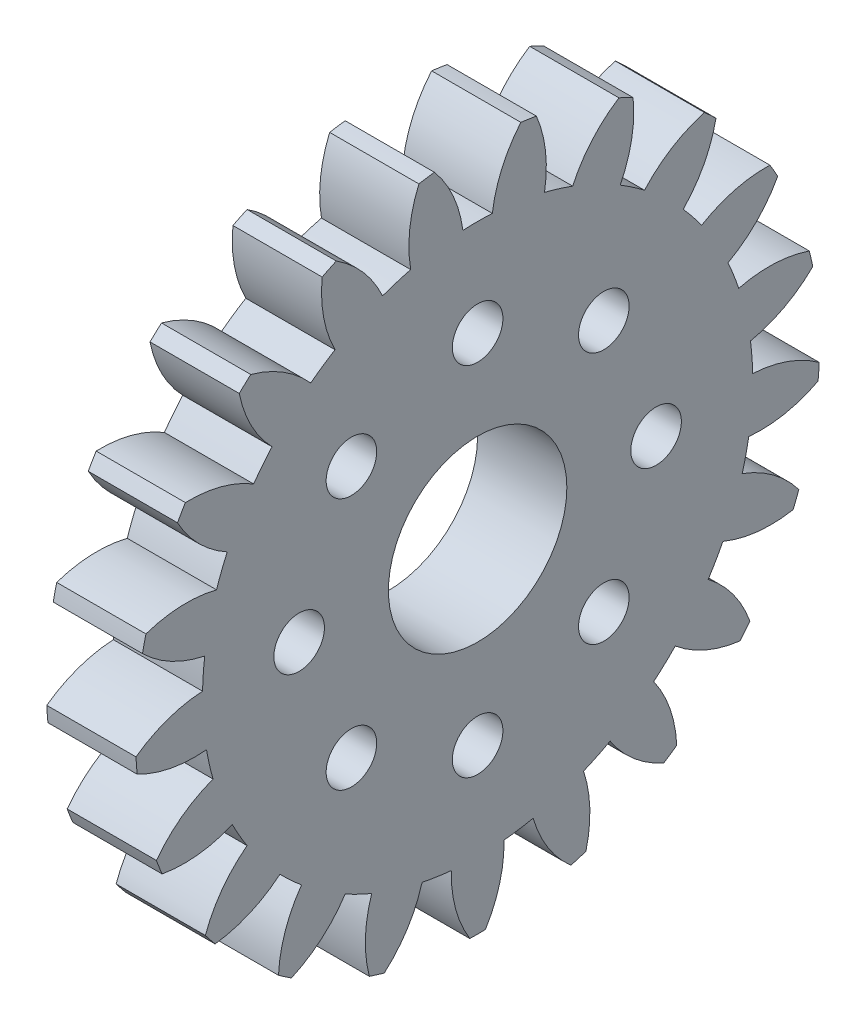
SolidWorks part; units mm, degrees
material "ﾎﾟﾘｵｷｼﾒﾁﾚﾝ(POM)ｱｾﾀｰﾙ共重合体"
ref_plane "Plane1" through (0, 0, 0) normal (0, 0, 1) x (1, 0, 0)
ref_plane "Plane2" through (0, 0, 0) normal (0, 1, 0) x (1, 0, 0)
ref_plane "Plane3" through (0, 0, 0) normal (1, 0, 0) x (0, 0, -1)
other "Configuration Table"
sketch "HoldingSke" plane through (0, 0, 0) normal (0, 1, 0) x (1, 0, 0)
  line L0 (0, 0) -> (0.9336, -0.3584)
  line L1 (-15, 0) -> (100, 0) construction
  line L2 (0, 0) -> (-2.1039, 2.3779)
  line L3 (0, 0) -> (-11.863, 4.5341)
  line L4 (0, 0) -> (8.0624, 3.0949)
  line L5 (0, 0) -> (-46.8476, -17.4728)
  line L6 (0, 0) -> (-2.4869, -1.6779)
  line L7 (-2.1039, 2.3779) -> (8.6586, 51.2059)
  line L8 (-76.2, 54.61) -> (-75.2, 54.61)
  line L9 (-71.009, 38.7566) -> (-53.1078, 45.2721)
  line L10 (-76.2, 71.12) -> (104.1128, 71.12)
  line L11 (0, 0) -> (-3, 0)
  line L12 (-76.2, 101.6) -> (-76.162, 101.6)
  line L13 (24.9733, 27.94) -> (52.9518, 28.4284)
  line L14 (24.9733, 27.94) -> (24.9743, 27.94)
  line L15 (24.9733, 27.94) -> (100.4006, 29.5858)
  line L16 (-63.627, -1) -> (-12.827, -1)
  circle A0 centre (0, 0) radius 4
  circle A1 centre (0, 0) radius 9.249
  circle A2 centre (0, 0) radius 37.5
  circle A3 centre (0, 0) radius 4
  dimension "MHD" = 18.498
  dimension "Hub_dia" = 75
  dimension "Bore" = 8
  dimension "MBD" = 8
  dimension "Num_teeth" = 21
  dimension "Pitch" = 1
  dimension "Overall_len" = 50
  dimension "Show_teeth" = 21
  dimension "Thickness" = 3
  dimension "OAL" = 50.0001
  dimension "T_dim" = 1
  dimension "Ap" = 20
  dimension "H" = 19.05
  dimension "Pitch_radius" = 180.3128
  dimension "Width" = 3
  dimension "Backlash" = 0.038
  dimension "Addendum_fac" = 1
  dimension "Dedendum_fac" = 1.25
  dimension "Clearance_fac" = 0.25
  dimension "Dedendum_add" = 0.001
  dimension "Module" = 1
sketch "BasProSke" plane through (0, 0, 0) normal (0, 1, 0) x (1, 0, 0)
  line L0 (-10, 0) -> (60, 0) construction
  line L1 (0, 0) -> (0, 11.5)
  line L2 (0, 0) -> (3, 0)
  line L3 (3, 0) -> (3, 11.5)
  line L4 (3, 11.5) -> (0, 11.5)
  dimension "Thickness" = 3
  dimension "Diameter" = 23
revolve "Base-Revolve" add sketch "BasProSke" angle 360 about L0
sketch "TooCutSke" plane through (0, 0, 0) normal (1, 0, 0) x (0, 0, -1)
  line L1 (0, 0) -> (0, 107) construction
  line L2 (0, 0) -> (-0.8511, 10.4654) construction
  line L3 (0, 0) -> (-3.1226, 20.7168) construction
  line L4 (-0.8511, 10.4654) -> (-1.5613, 10.3584) construction
  arc A0 (0.4953, 9.2357) -> (-0.4953, 9.2357) centre (0, 0) ccw
  arc A1 (1.4725, 11.431) -> (-1.4725, 11.431) centre (0, 0) ccw
  circle A2 centre (0, 0) radius 10.5 construction
  circle A3 centre (0, 0) radius 9.8668 construction
  arc A4 (-0.4953, 9.2357) -> (-1.4725, 11.431) centre (-4.6605, 8.6967) ccw
  arc A5 (1.4725, 11.431) -> (0.4953, 9.2357) centre (4.6605, 8.6967) ccw
  dimension "Root_dia" = 18.498
  dimension "Overcut_dia" = 23.0508
  dimension "Pitch_dia" = 21
  dimension "Base_dia" = 19.7335
  dimension "Flank_rad" = 4.2
  dimension "Half_ang" = 8.571
  dimension "Half_CT" = 0.7182
extrude "ToothCut" cut sketch "TooCutSke" along normal through all
fillet "Breaks" [suppressed] radius 0.02
fillet "RootFillets" [suppressed] radius 0.251
pattern_circular "TeethCuts" count 21 every 17.143 about axis through (-10, 0, 0) along (1, 0, 0) of "ToothCut", "RootFillets", "Breaks"
sketch "HubNeaOneSke" plane through (0, 0, 0) normal (-1, 0, 0) x (0, 0, 1)
  circle A0 centre (0, 0) radius 9.249
  dimension "Diameter" = 18.498
extrude "HubNearOne" [suppressed] add sketch "HubNeaOneSke" along normal blind 47.0001
sketch "HubNeaBotSke" plane through (0, 0, 0) normal (-1, 0, 0) x (0, 0, 1)
  circle A0 centre (0, 0) radius 9.249
  dimension "Diameter" = 18.498
extrude "HubNearBoth" [suppressed] add sketch "HubNeaBotSke" along normal blind 23.5
ref_plane "FarPln" through (3, 0, 0) normal (1, 0, 0) x (0, 0, -1)
sketch "HubFarSke" plane through (3, 0, 0) normal (1, 0, 0) x (0, 0, -1)
  circle A0 centre (0, 0) radius 9.249
  dimension "Diameter" = 18.498
extrude "HubFar" [suppressed] add sketch "HubFarSke" along normal blind 23.5
sketch "BorSke" plane through (0, 0, 0) normal (1, 0, 0) x (0, 0, -1)
  circle A0 centre (0, 0) radius 4
  dimension "Diameter" = 8
extrude "Bore" cut sketch "BorSke" along normal mid plane 100.0001
sketch "KeySke" plane through (0, 0, 0) normal (1, 0, 0) x (0, 0, -1)
  line L0 (-1, 0) -> (-1, 5)
  line L1 (-1, 5) -> (1, 5)
  line L2 (1, 5) -> (1, 0)
  line L3 (0, 0) -> (0, 34) construction
  line L4 (-1, 0) -> (1, 0)
  dimension "Offset" = 5
  dimension "Width" = 2
extrude "Keyway" [suppressed] cut sketch "KeySke" along normal mid plane 100.0001
pattern_circular "Keyway2" [suppressed] count 2 every 90 about axis through (-10, 0, 0) along (1, 0, 0)
sketch "ｽｹｯﾁ1" plane through (0, 0, 0) normal (-1, 0, 0) x (0, 0, 1)
  circle A0 centre (0, 0) radius 4 construction
  circle A1 centre (0, 0) radius 4
extrude "ﾎﾞｽ - 押し出し1" add sketch "ｽｹｯﾁ1" against normal up to surface (3 mm away) up to face at (3, 0, 4)
sketch "ｽｹｯﾁ2" plane through (3, 0, 0) normal (1, 0, 0) x (0, 0, -1)
  circle A0 centre (0, 0) radius 3
  circle A1 centre (0, 0) radius 6 construction
  circle A2 centre (0, 6) radius 0.85
  circle A3 centre (4.2426, 4.2426) radius 0.85
  circle A4 centre (6, 0) radius 0.85
  circle A5 centre (4.2426, -4.2426) radius 0.85
  circle A6 centre (0, -6) radius 0.85
  circle A7 centre (-4.2426, -4.2426) radius 0.85
  circle A8 centre (-6, 0) radius 0.85
  circle A9 centre (-4.2426, 4.2426) radius 0.85
  point P22 (0, 0)
  point P23 (0, 0)
  dimension "D1" = 12
  dimension "D2" = 1.7
  dimension "D3" = 6
  dimension "D4" = 8
extrude "ｶｯﾄ - 押し出し1" cut sketch "ｽｹｯﾁ2" against normal through all
equation "' \"Module@HoldingSke\" = 6.35"
equation "' \"Num_teeth@HoldingSke\" = 12"
equation "' \"Ap@HoldingSke\" =  20"
equation "' \"Ap@HoldingSke\" = 20"
equation "' \"Width@HoldingSke\" = 0.5 * 25.4"
equation "' \"Hub_dia@HoldingSke\"= 1 * 25.4"
equation "' \"Hub_dia@HoldingSke\" = 1 * 25.4"
equation "' \"Overall_len@HoldingSke\" = 1.0 * 25.4"
equation "' \"Bore@HoldingSke\" = 0.75 * 25.4"
equation "' \"T_dim@HoldingSke\" = 0.1 * 25.4"
equation "' \"Width@KeySke\" = 0.25 * 25.4"
equation "' \"Show_teeth@HoldingSke\" = 13"
equation "' \"Backlash@HoldingSke\" = 0.009 * 25.4"
equation "' \"Addendum_fac@HoldingSke\" = 1.0"
equation "' \"Dedendum_fac@HoldingSke\" = 1.25"
equation "' \"Dedendum_add@HoldingSke\" = 0.00005 * 25.4"
equation "' \"Clearance_fac@HoldingSke\" = 0.25"
equation "\"Pitch@HoldingSke\" = 1 / \"Module@HoldingSke\""
equation "\"Overcut_dia@TooCutSke\" = (\"Num_teeth@HoldingSke\" + 2 * \"Addendum_fac@HoldingSke\") / \"Pitch@HoldingSke\" + 0.002 * 25.4"
equation "\"Pitch_dia@TooCutSke\" = \"Num_teeth@HoldingSke\" / \"Pitch@HoldingSke\""
equation "\"Base_dia@TooCutSke\" = \"Num_teeth@HoldingSke\" / \"Pitch@HoldingSke\" * cos((\"Ap@HoldingSke\"  * 3.14159265 / 180))"
equation "\"Root_dia@TooCutSke\" = (\"Num_teeth@HoldingSke\" + 2) / \"Pitch@HoldingSke\" - 2 * (\"Addendum_fac@HoldingSke\" + \"Dedendum_fac@HoldingSke\") / \"Pitch@HoldingSke\" - \"Dedendum_add@HoldingSke\" * 2"
equation "\"Half_ang@TooCutSke\" = 180 / \"Num_teeth@HoldingSke\""
equation "\"Half_CT@TooCutSke\" = \"Num_teeth@HoldingSke\" / \"Pitch@HoldingSke\" * sin((3.14159265 / 2 / \"Num_teeth@HoldingSke\")) / 2 - 7 * \"Backlash@HoldingSke\" / 4"
equation "\"Flank_rad@TooCutSke\" = \"Num_teeth@HoldingSke\" / \"Pitch@HoldingSke\" / 5"
equation "\"Radius@RootFillets\" = \"Clearance_fac@HoldingSke\" / \"Pitch@HoldingSke\" + \"Dedendum_add@HoldingSke\""
equation "\"Break_rad@Breaks\" = 0.02 / \"Pitch@HoldingSke\""
equation "\"Thickness@HoldingSke\" = \"Width@HoldingSke\""
equation "\"OAL@HoldingSke\" = \"Thickness@HoldingSke\""
equation "\"MHD@HoldingSke\" = (\"Num_teeth@HoldingSke\" + 2) / \"Pitch@HoldingSke\" - 2 * (\"Addendum_fac@HoldingSke\" + \"Dedendum_fac@HoldingSke\")  / \"Pitch@HoldingSke\" - \"Dedendum_add@HoldingSke\" * 2"
equation "\"MBD@HoldingSke\" = (\"Num_teeth@HoldingSke\" + 2) / \"Pitch@HoldingSke\" - 2 * (\"Addendum_fac@HoldingSke\" + \"Dedendum_fac@HoldingSke\")  / \"Pitch@HoldingSke\" - \"Dedendum_add@HoldingSke\" * 2 - 0.002 * 25.4"
equation "\"MHD@HoldingSke\" = ((sgn( \"MHD@HoldingSke\" - \"Hub_dia@HoldingSke\" )-1)*( \"MHD@HoldingSke\" - \"Hub_dia@HoldingSke\" ))/-2+ \"Hub_dia@HoldingSke\""
equation "\"MBD@HoldingSke\" = ((sgn( \"MBD@HoldingSke\" - \"Bore@HoldingSke\" )-1)*( \"MBD@HoldingSke\" - \"Bore@HoldingSke\" ))/-2+ \"Bore@HoldingSke\""
equation "\"OAL@HoldingSke\" = ((sgn( \"OAL@HoldingSke\" - \"Overall_len@HoldingSke\" )+1)*( \"OAL@HoldingSke\" - \"Overall_len@HoldingSke\" ))/2 + \"Overall_len@HoldingSke\" + 0.000002 * 25.4"
equation "\"Num_teeth@TeethCuts\" = int( \"Show_teeth@HoldingSke\" ) + 1"
equation "\"Num_teeth@TeethCuts\" = ((sgn( \"Num_teeth@TeethCuts\" - \"Num_teeth@HoldingSke\" )-1)*( \"Num_teeth@TeethCuts\" - \"Num_teeth@HoldingSke\" ))/-2+ \"Num_teeth@HoldingSke\""
equation "\"Num_teeth@TeethCuts\" = ((sgn( \"Num_teeth@TeethCuts\" - 2.0)+1)*( \"Num_teeth@TeethCuts\" - 2.0))/2 +2.0"
equation "\"Angle@TeethCuts\" = 360.0 / \"Num_teeth@HoldingSke\""
equation "\"Diameter@BasProSke\" = (\"Num_teeth@HoldingSke\" + 2 * \"Addendum_fac@HoldingSke\") / \"Pitch@HoldingSke\""
equation "\"Thickness@BasProSke\"  = \"Thickness@HoldingSke\""
equation "' \"Fillet_rad@BasProSke\" =  \"Thickness@HoldingSke\" * 0.05"
equation "' \"Fillet_rad@BasProSke\" = \"Thickness@HoldingSke\" * 0.05"
equation "\"MHD@HoldingSke\" = ((sgn( \"MHD@HoldingSke\" - \"Root_dia@TooCutSke\" )-1)*( \"MHD@HoldingSke\" - \"Root_dia@TooCutSke\" ))/-2+ \"Root_dia@TooCutSke\""
equation "\"Diameter@HubNeaOneSke\" = \"MHD@HoldingSke\""
equation "\"Length@HubNearOne\" = \"OAL@HoldingSke\" - \"Thickness@BasProSke\""
equation "\"Diameter@HubNeaBotSke\" = \"MHD@HoldingSke\""
equation "\"Length@HubNearBoth\" = ( \"OAL@HoldingSke\" - \"Thickness@BasProSke\" ) / 2.0"
equation "\"Thickness@FarPln\" = \"Thickness@BasProSke\""
equation "\"Diameter@HubFarSke\" = \"MHD@HoldingSke\""
equation "\"Length@HubFar\" = ( \"OAL@HoldingSke\" - \"Thickness@BasProSke\" ) / 2.0"
equation "\"Diameter@BorSke\" = \"MBD@HoldingSke\""
equation "\"D1@Bore\" = \"OAL@HoldingSke\" * 2.0"
equation "\"D1@Keyway\" = \"OAL@HoldingSke\" * 2.0"
equation "\"Offset@KeySke\" = \"T_dim@HoldingSke\" + \"MBD@HoldingSke\" / 2.0"
